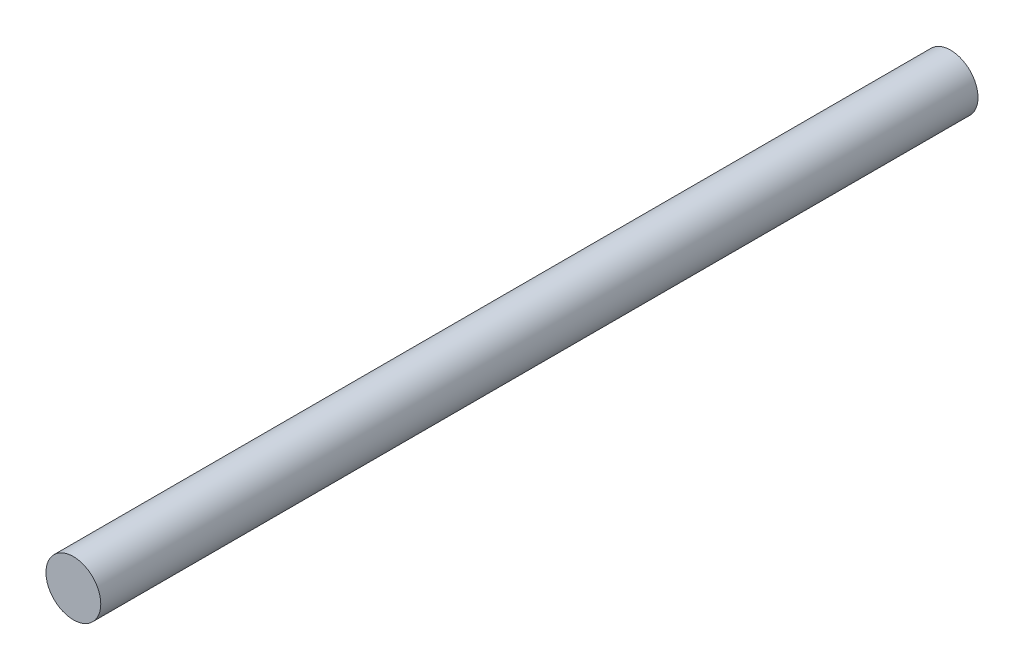
SolidWorks part; units mm, degrees
material "Plain Carbon Steel"
ref_plane "Front Plane" through (0, 0, 0) normal (0, 0, 1) x (1, 0, 0)
ref_plane "Top Plane" through (0, 0, 0) normal (0, 1, 0) x (1, 0, 0)
ref_plane "Right Plane" through (0, 0, 0) normal (1, 0, 0) x (0, 0, -1)
sketch "Sketch1" plane through (0, 0, 0) normal (0, 0, 1) x (1, 0, 0)
  circle A0 centre (0, 0) radius 3.175
  dimension "D1" = 6.35
extrude "Boss-Extrude1" add sketch "Sketch1" along normal mid plane 101.6 contours A0
